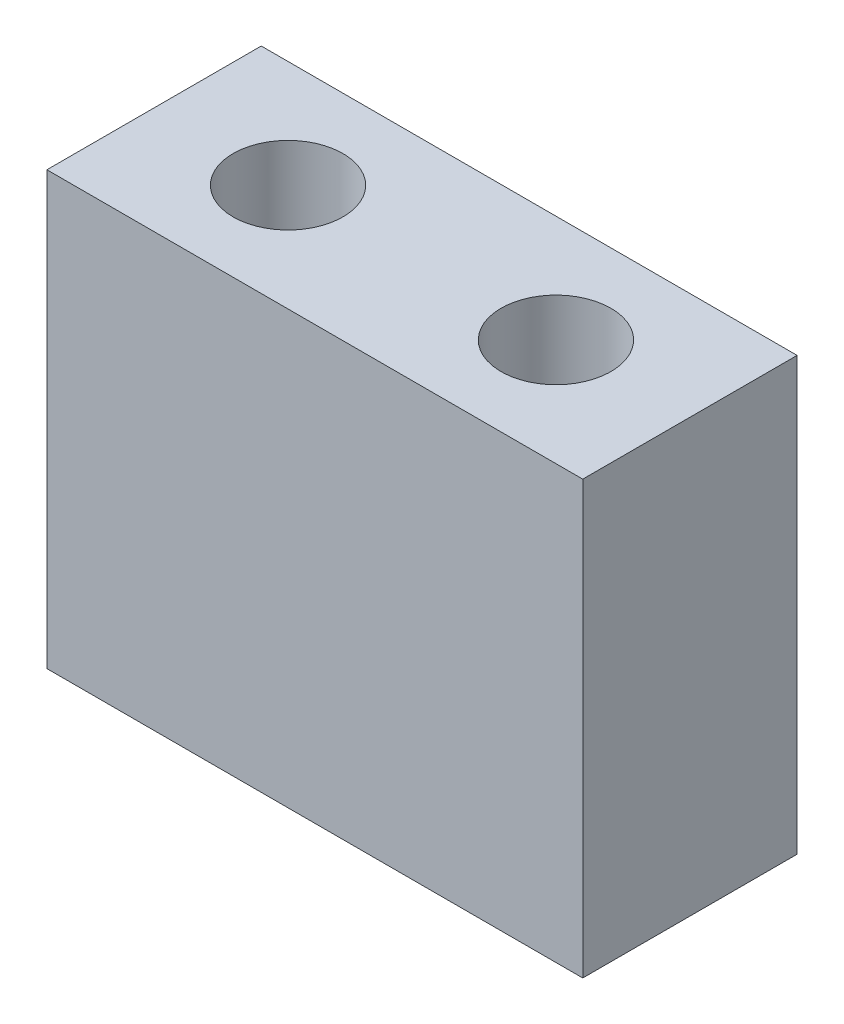
SolidWorks part; units mm, degrees
material "PLA"
ref_plane "Front Plane" through (0, 0, 0) normal (0, 0, 1) x (1, 0, 0)
ref_plane "Top Plane" through (0, 0, 0) normal (0, 1, 0) x (1, 0, 0)
ref_plane "Right Plane" through (0, 0, 0) normal (1, 0, 0) x (0, 0, -1)
sketch "Sketch1" plane through (0, 0, 0) normal (0, 1, 0) x (1, 0, 0)
  line L1 (-10, -4) -> (10, -4)
  line L2 (-10, -4) -> (-10, 4)
  line L3 (-10, 4) -> (10, 4)
  line L4 (10, -4) -> (10, 4)
  line L5 (-10, -4) -> (10, 4) construction
  line L6 (-10, 4) -> (10, -4) construction
  point P0 (0, 0)
  dimension "D1" = 20
  dimension "D2" = 8
extrude "Boss-Extrude1" add sketch "Sketch1" along normal blind 16.125
sketch "Sketch2" plane through (0, 16.125, 0) normal (0, 1, 0) x (1, 0, 0)
  line L0 (0, 4) -> (0, -4) construction
  line L1 (10, 4) -> (-10, 4) construction
  line L2 (-10, -4) -> (10, -4) construction
  line L3 (-10, 0) -> (10, 0) construction
  line L4 (-10, 4) -> (-10, -4) construction
  line L5 (10, -4) -> (10, 4) construction
  circle A0 centre (-5, 0) radius 2.05
  circle A1 centre (5, 0) radius 2.05
  dimension "D1" = 4.1
  dimension "D2" = 5
extrude "Cut-Extrude1" cut sketch "Sketch2" against normal up to surface (16.125 mm away) up to face at (0, 0, 0)
